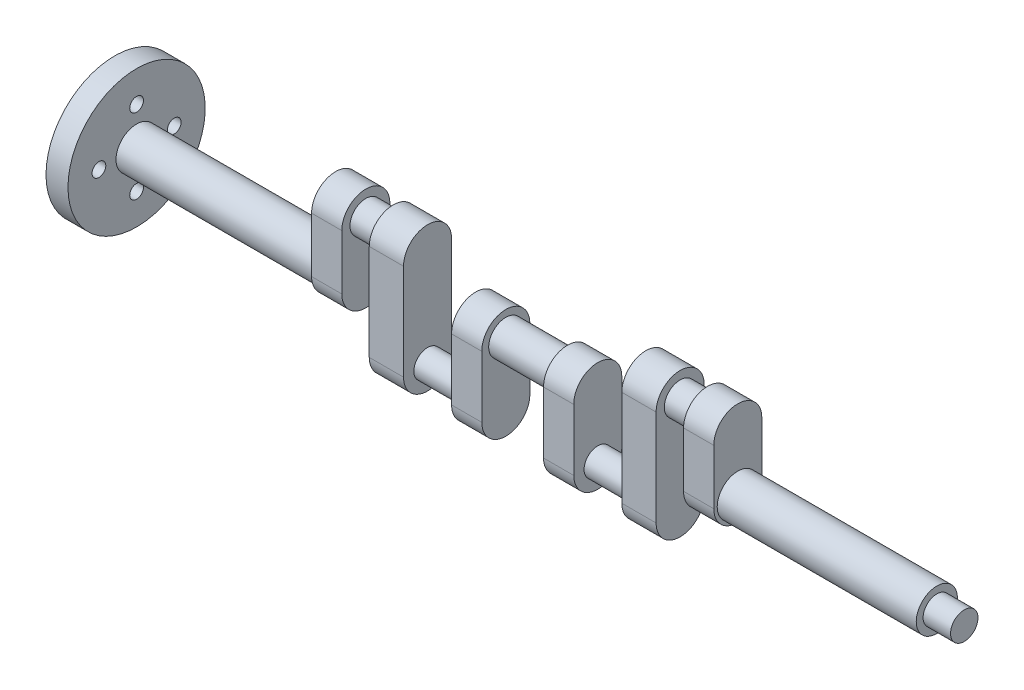
SolidWorks part; units mm, degrees
material "1060 Alloy"
ref_plane "Front Plane" through (0, 0, 0) normal (0, 0, 1) x (1, 0, 0)
ref_plane "Top Plane" through (0, 0, 0) normal (0, 1, 0) x (1, 0, 0)
ref_plane "Right Plane" through (0, 0, 0) normal (1, 0, 0) x (0, 0, -1)
sketch "Sketch1" plane through (0, 0, 0) normal (1, 0, 0) x (0, 0, -1)
  circle A0 centre (0, 0) radius 10
  dimension "D1" = 20
extrude "Boss-Extrude1" add sketch "Sketch1" against normal blind 20 contours A0
sketch "Sketch2" plane through (-20, 0, 0) normal (-1, 0, 0) x (0, 0, 1)
  circle A0 centre (0, 0) radius 15
  dimension "D1" = 30
extrude "Boss-Extrude2" add sketch "Sketch2" along normal blind 145
sketch "Sketch3" plane through (-165, 0, 0) normal (-1, 0, 0) x (0, 0, 1)
  line L0 (-17.5, 40) -> (-17.5, 0)
  line L1 (17.5, 40) -> (17.5, 0)
  arc A0 (-17.5, 0) -> (17.5, 0) centre (0, 0) ccw
  arc A1 (17.5, 40) -> (-17.5, 40) centre (0, 40) ccw
  point P1 (0, 0)
  dimension "D1" = 35
  dimension "D2" = 40
extrude "Boss-Extrude3" add sketch "Sketch3" along normal blind 22
sketch "Sketch4" plane through (-187, 0, 0) normal (-1, 0, 0) x (0, 0, 1)
  circle A0 centre (0, 40) radius 11.54
  dimension "D1" = 40
extrude "Boss-Extrude4" add sketch "Sketch4" along normal blind 20
sketch "Sketch5" plane through (-207, 0, 0) normal (-1, 0, 0) x (0, 0, 1)
  line L2 (-17.5, 40) -> (-17.5, -30)
  line L4 (17.5, 40) -> (17.5, -30)
  arc A2 (17.5, 40) -> (-17.5, 40) centre (0, 40) ccw
  arc A3 (-17.5, -30) -> (17.5, -30) centre (0, -30) ccw
  dimension "D1" = 70
  dimension "D2" = 70
extrude "Boss-Extrude7" add sketch "Sketch5" along normal blind 25 contours A2 L2 A3 L4
sketch "Sketch6" plane through (-232, 0, 0) normal (-1, 0, 0) x (0, 0, 1)
  circle A0 centre (0, -30) radius 10
  point P5 (52.4034, -2.8339)
  dimension "D2" = 20
  dimension "D1" = 30
extrude "Boss-Extrude8" add sketch "Sketch6" along normal blind 35
sketch "Sketch7" plane through (-267, 0, 0) normal (-1, 0, 0) x (0, 0, 1)
  line L3 (17.4991, 14.8223) -> (17.5, -30)
  line L4 (-17.5, 15) -> (-17.5, -30)
  arc A1 (17.4991, 14.8223) -> (-17.5, 15) centre (0, 15) ccw
  arc A2 (17.5, -30) -> (-17.5, -30) centre (0, -30) cw
  arc A3 (-17.5, -30) -> (17.5, -30) centre (0, -30) ccw construction
  dimension "D1" = 15
extrude "Boss-Extrude11" add sketch "Sketch7" along normal blind 22 contours L4 A2 L3 A1
sketch "Sketch8" plane through (-289, 0, 0) normal (-1, 0, 0) x (0, 0, 1)
  circle A0 centre (0, 15) radius 12.5
  dimension "D1" = 25
extrude "Boss-Extrude12" add sketch "Sketch8" along normal blind 22.5
ref_plane "Plane3" through (-311.5, 0, 0) normal (-1, 0, 0) x (0, 0, 1)
mirror "Mirror5" about plane through (-311.5, 15, 0) normal (-1, 0, 0) of "Boss-Extrude12"
mirror "Mirror6" about plane through (-311.5, 0, 0) normal (-1, 0, 0) of "Boss-Extrude11"
mirror "Mirror7" about plane through (-311.5, 0, 0) normal (-1, 0, 0) of "Boss-Extrude3", "Boss-Extrude4", "Boss-Extrude7", "Boss-Extrude8"
mirror "Mirror8" about plane through (-311.5, 0, 0) normal (-1, 0, 0) of "Boss-Extrude7"
mirror "Mirror9" about plane through (-311.5, 0, 0) normal (-1, 0, 0) of "Boss-Extrude4"
mirror "Mirror10" about plane through (-311.5, 0, 0) normal (-1, 0, 0) of "Boss-Extrude3"
mirror "Mirror11" about plane through (-311.5, 0, 0) normal (-1, 0, 0) of "Boss-Extrude2"
sketch "Sketch9" plane through (-603, 0, 0) normal (-1, 0, 0) x (0, 0, 1)
  circle A0 centre (0, 0) radius 50
  circle A1 centre (0, 27.4369) radius 5
  circle A2 centre (27.4369, 0) radius 5
  circle A3 centre (0, -27.4369) radius 5
  circle A4 centre (-27.4369, 0) radius 5
  point P14 (0, 0)
  dimension "D1" = 10
  dimension "D3" = 100
  dimension "D2" = 4
extrude "Boss-Extrude13" add sketch "Sketch9" along normal blind 16 contours A0 | A2 | A4 | A1 | A3
